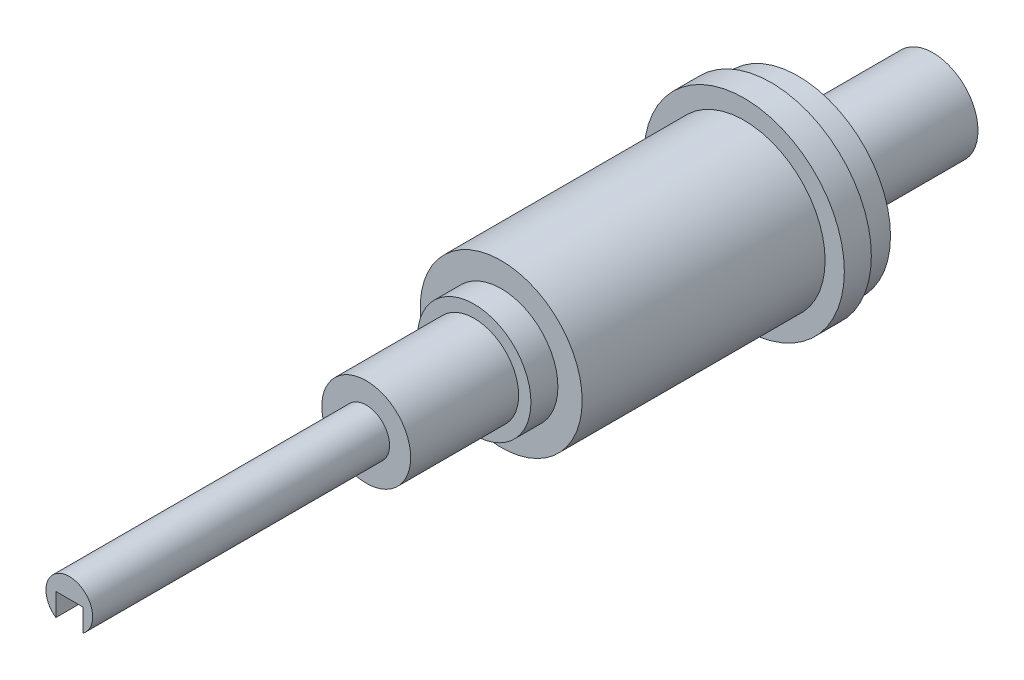
SolidWorks part; units mm, degrees
ref_plane "Front Plane" through (0, 0, 0) normal (0, 0, 1) x (1, 0, 0)
ref_plane "Top Plane" through (0, 0, 0) normal (0, 1, 0) x (1, 0, 0)
ref_plane "Right Plane" through (0, 0, 0) normal (1, 0, 0) x (0, 0, -1)
sketch "Sketch1" plane through (0, 0, 0) normal (1, 0, 0) x (0, 0, -1)
  line L0 (0, 0) -> (0, 5.4922)
  line L2 (69.85, 5.4922) -> (69.85, 10.453)
  line L3 (69.85, 10.453) -> (95.25, 10.453)
  line L4 (95.25, 10.453) -> (95.25, 13.3402)
  line L6 (0, 0) -> (203.2, 0)
  line L7 (158.75, 19.05) -> (158.75, 23.5795)
  line L8 (158.75, 23.5795) -> (165.1, 23.5795)
  line L9 (165.1, 23.5795) -> (165.1, 21.7352)
  line L10 (165.1, 21.7352) -> (171.45, 21.7352)
  line L11 (171.45, 21.7352) -> (171.45, 10.569)
  line L12 (171.45, 10.569) -> (203.2, 10.569)
  line L13 (203.2, 10.569) -> (203.2, 0)
  line L14 (171.45, 10.569) -> (158.75, 10.569) construction
  line L15 (95.25, 10.453) -> (107.95, 10.453) construction
  line L16 (69.85, 5.4922) -> (0, 5.4922)
  line L17 (69.85, 5.4922) -> (76.2, 5.4922) construction
  line L18 (95.25, 13.3402) -> (101.6, 13.3402)
  line L19 (101.6, 13.3402) -> (101.6, 19.05)
  line L20 (101.6, 19.05) -> (158.75, 19.05)
  point P3 (0, 0)
  point P17 (171.45, 16.1521)
  dimension "D1" = 5.4922
  dimension "D2" = 10.453
  dimension "D9" = 76.2
  dimension "D10" = 31.75
  dimension "D8" = 50.8
  dimension "D7" = 76.2
  dimension "D11" = 6.35
  dimension "D12" = 19.05
  dimension "D3" = 6.35
  dimension "D4" = 13.3402
  dimension "D5" = 19.05
  dimension "D6" = 23.5795
  dimension "D13" = 21.7352
  dimension "D14" = 10.569
revolve "Revolve1" add sketch "Sketch1" angle 360 about L6
ref_plane "Plane1" through (0, -5.4922, 0) normal (0, -1, 0) x (-1, 0, 0)
sketch "Sketch2" plane through (0, -5.4922, 0) normal (0, -1, 0) x (-1, 0, 0)
  line L0 (-5.4922, 0) -> (5.4922, 0) construction
  line L1 (-3.175, 0) -> (3.175, 0)
  line L2 (-3.175, 0) -> (-3.175, 50.8)
  line L3 (-3.175, 50.8) -> (3.175, 50.8)
  line L4 (3.175, 0) -> (3.175, 50.8)
  point P6 (0, 0)
  dimension "D1" = 50.8
  dimension "D2" = 6.35
extrude "Cut-Extrude1" cut sketch "Sketch2" against normal blind 6.35
ref_plane "Plane2" through (0, -19.05, 0) normal (0, -1, 0) x (-1, 0, 0)
sketch "Sketch3" plane through (0, -19.05, 0) normal (0, -1, 0) x (-1, 0, 0)
  line L0 (0, 158.75) -> (0, 152.4) construction
  line L1 (-3.175, 114.3) -> (3.175, 114.3)
  line L2 (-3.175, 114.3) -> (-3.175, 152.4)
  line L3 (-3.175, 152.4) -> (3.175, 152.4)
  line L4 (3.175, 114.3) -> (3.175, 152.4)
  line L5 (0, 114.3) -> (0, 107.95) construction
  point P4 (0, 114.3)
  point P7 (0, 158.75)
  point P8 (0, 107.95)
  dimension "D1" = 6.35
  dimension "D2" = 6.35
extrude "Cut-Extrude2" cut sketch "Sketch3" against normal blind 6.35 contours L4 L3 L2 L1
equation "\"Di1\"=0.43246"
equation "\"D1@Sketch1\"=\"Di1\"/2"
equation "\"Di2\"=0.823069"
equation "\"D2@Sketch1\"=\"Di2\"/2"
equation "\"Di3\"=1.05041"
equation "\"Di4\"= 1.5"
equation "\"Di5\"=1.85665"
equation "\"Di6\"=1.71143"
equation "\"FaceWidth\"= 2"
equation "\"D8@Sketch1\"=\"FaceWidth\""
equation "\"D4@Sketch1\"=\"Di3\"/2"
equation "\"D5@Sketch1\"=\"Di4\"/2"
equation "\"D6@Sketch1\"=\"Di5\"/2"
equation "\"D13@Sketch1\"=\"Di6\"/2"
equation "\"Di7\"=0.832202"
equation "\"D14@Sketch1\"=\"Di7\"/2"
